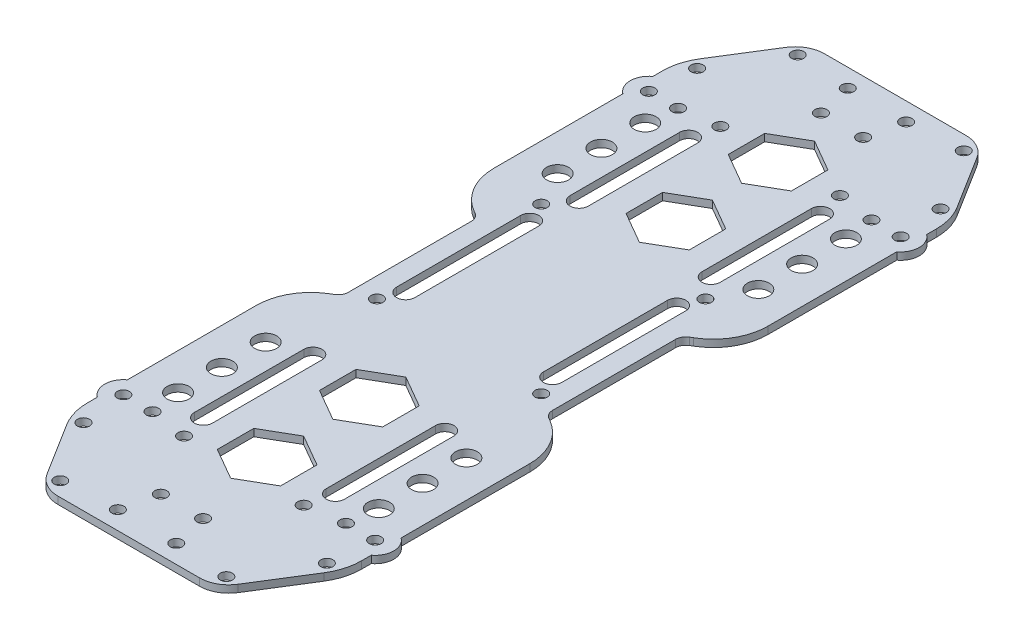
SolidWorks part; units mm, degrees
ref_plane "Front Plane" through (0, 0, 0) normal (0, 0, 1) x (1, 0, 0)
ref_plane "Top Plane" through (0, 0, 0) normal (0, 1, 0) x (1, 0, 0)
ref_plane "Right Plane" through (0, 0, 0) normal (1, 0, 0) x (0, 0, -1)
sketch "Sketch1" plane through (0, 0, 0) normal (0, 1, 0) x (1, 0, 0)
  line L0 (37.5251, 78.755) -> (37.5251, 32.6348)
  line L2 (-200, -200) -> (200, -200) construction
  line L7 (-200, -200) -> (-200, 200) construction
  line L11 (200, -200) -> (200, 200) construction
  line L14 (-200, -200) -> (200, 200) construction
  line L17 (0, 0) -> (60, 0) construction
  line L23 (0, 120) -> (0, -120) construction
  line L24 (0, 0) -> (-60, 0) construction
  line L69 (29.4047, 19.2862) -> (30.0251, 19.6444)
  line L70 (-30, -19.6299) -> (-29.4047, -19.2862)
  line L71 (-28, -16.8532) -> (-28, 16.8532)
  line L73 (37.5251, -32.6348) -> (37.5251, -78.755)
  line L74 (-29.4047, 19.2862) -> (-30, 19.6299)
  line L78 (28, -16.8532) -> (28, 16.8532)
  line L79 (30.0251, -19.6444) -> (29.4047, -19.2862)
  line L80 (-37.5, -32.6203) -> (-37.5, -78.7951)
  line L81 (-60, 36.9504) -> (-67.2154, 32.7846) [skipped]
  line L82 (-92, 0) -> (-92, -18.4752) [skipped]
  line L83 (-76, -27.7128) -> (-60, -36.9504) [skipped]
  line L84 (-200, 200) -> (200, -200) construction
  line L85 (-200, 200) -> (200, 200) construction
  line L86 (-22.7528, 101.0355) -> (-33.3512, 84.0745) construction
  line L87 (-28.052, 92.555) -> (-200, 200) construction
  line L88 (-33.3512, 84.0745) -> (-16.3903, 73.4761) construction
  line L89 (-16.3903, 73.4761) -> (-5.7919, 90.4371) construction
  line L90 (16.3903, 73.4761) -> (5.7919, 90.4371) construction
  line L91 (-19.3786, 105) -> (19.3786, 105)
  line L92 (-35.2207, 86.7439) -> (-26.163, 101.2394)
  line L93 (35.2458, 86.7038) -> (26.163, 101.2394)
  line L94 (-37.5, 78.7951) -> (-37.5, 32.6203)
  line L95 (35.2458, -86.7038) -> (26.163, -101.2394)
  line L96 (-19.3786, -105) -> (19.3786, -105)
  line L97 (-35.2207, -86.7439) -> (-26.163, -101.2394)
  line L98 (33.3512, 84.0745) -> (16.3903, 73.4761) construction
  line L99 (22.7528, 101.0355) -> (33.3512, 84.0745) construction
  line L100 (22.7528, -101.0355) -> (33.3512, -84.0745) construction
  line L101 (33.3512, -84.0745) -> (16.3903, -73.4761) construction
  line L102 (16.3903, -73.4761) -> (5.7919, -90.4371) construction
  line L103 (-16.3903, -73.4761) -> (-5.7919, -90.4371) construction
  line L104 (-33.3512, -84.0745) -> (-16.3903, -73.4761) construction
  line L105 (-22.7528, -101.0355) -> (-33.3512, -84.0745) construction
  circle A7 centre (200, 200) radius 177.8 construction
  circle A8 centre (-200, 200) radius 177.8 construction
  circle A9 centre (-200, -200) radius 177.8 construction
  circle A10 centre (200, -200) radius 177.8 construction
  circle A29 centre (-27.4977, 64) radius 3
  circle A30 centre (-27.4989, 52) radius 3
  circle A31 centre (-27.5, 40) radius 3
  circle A70 centre (27.5, 40) radius 3
  circle A71 centre (27.4989, 52) radius 3
  circle A72 centre (27.4977, 64) radius 3
  circle A73 centre (27.4977, -64) radius 3
  circle A74 centre (27.4989, -52) radius 3
  circle A75 centre (27.5, -40) radius 3
  circle A76 centre (-27.5, -40) radius 3
  circle A77 centre (-27.4989, -52) radius 3
  circle A78 centre (-27.4977, -64) radius 3
  circle A79 centre (-34.4977, 72) radius 1.65
  circle A80 centre (34.4977, 72) radius 1.65
  circle A82 centre (-34.4977, -72) radius 1.65
  circle A84 centre (-22.7528, 101.0355) radius 1.65
  circle A92 centre (22.7528, 101.0355) radius 3 construction
  circle A94 centre (5.7919, 90.4371) radius 3 construction
  circle A96 centre (16.3903, 73.4761) radius 3 construction
  circle A97 centre (33.3512, 84.0745) radius 3 construction
  circle A100 centre (33.3512, -84.0745) radius 3 construction
  circle A102 centre (16.3903, -73.4761) radius 3 construction
  circle A104 centre (22.7528, -101.0355) radius 3 construction
  circle A106 centre (5.7919, -90.4371) radius 3 construction
  circle A108 centre (-5.7919, -90.4371) radius 3 construction
  circle A110 centre (-16.3903, -73.4761) radius 3 construction
  circle A111 centre (-33.3512, -84.0745) radius 3 construction
  circle A114 centre (-22.7528, -101.0355) radius 3 construction
  arc A115 (26.163, 101.2394) -> (19.3786, 105) centre (19.3786, 97) ccw
  arc A116 (-19.3786, 105) -> (-26.163, 101.2394) centre (-19.3786, 97) ccw
  arc A117 (35.2458, 86.7038) -> (37.5251, 78.755) centre (22.5251, 78.755) cw
  arc A118 (-35.2207, 86.7439) -> (-37.5, 78.7951) centre (-22.5, 78.7951) ccw
  arc A119 (35.2458, -86.7038) -> (37.5251, -78.755) centre (22.5251, -78.755) ccw
  arc A120 (26.163, -101.2394) -> (19.3786, -105) centre (19.3786, -97) cw
  arc A121 (-19.3786, -105) -> (-26.163, -101.2394) centre (-19.3786, -97) cw
  arc A122 (-35.2207, -86.7439) -> (-37.5, -78.7951) centre (-22.5, -78.7951) cw
  arc A123 (-30, 19.6299) -> (-37.5, 32.6203) centre (-22.5, 32.6203) cw
  arc A124 (30.0251, 19.6444) -> (37.5251, 32.6348) centre (22.5251, 32.6348) ccw
  arc A125 (37.5251, -32.6348) -> (30.0251, -19.6444) centre (22.5251, -32.6348) ccw
  arc A126 (-30, -19.6299) -> (-37.5, -32.6203) centre (-22.5, -32.6203) ccw
  arc A127 (-28, 16.8532) -> (-29.4047, 19.2862) centre (-30.8094, 16.8532) ccw
  arc A128 (29.4047, 19.2862) -> (28, 16.8532) centre (30.8094, 16.8532) ccw
  arc A129 (28, -16.8532) -> (29.4047, -19.2862) centre (30.8094, -16.8532) ccw
  arc A130 (-29.4047, -19.2862) -> (-28, -16.8532) centre (-30.8094, -16.8532) ccw
  circle A131 centre (-33.3512, 84.0745) radius 1.65
  circle A132 centre (-5.7919, 90.4371) radius 1.65
  circle A133 centre (-16.3903, 73.4761) radius 1.65
  circle A134 centre (16.3903, 73.4761) radius 1.65
  circle A135 centre (5.7919, 90.4371) radius 1.65
  circle A136 centre (33.3512, 84.0745) radius 1.65
  circle A137 centre (22.7528, 101.0355) radius 1.65
  circle A138 centre (-16.3903, -73.4761) radius 1.65
  circle A139 centre (16.3903, -73.4761) radius 1.65
  circle A140 centre (33.3512, -84.0745) radius 3 construction
  circle A141 centre (5.7919, -90.4371) radius 3 construction
  circle A142 centre (22.7528, -101.0355) radius 3 construction
  circle A143 centre (22.7528, -101.0355) radius 1.65
  circle A144 centre (33.3512, -84.0745) radius 1.65
  circle A145 centre (5.7919, -90.4371) radius 1.65
  circle A146 centre (-5.7919, -90.4371) radius 1.65
  circle A147 centre (-33.3512, -84.0745) radius 1.65
  circle A148 centre (-22.7528, -101.0355) radius 1.65
  circle A149 centre (34.4977, -72) radius 1.65
  point P22 (0, 0)
  point P26 (-200, 200)
  point P54 (0, 0)
  point P151 (-28, 18.4752)
  point P154 (28, 18.4752)
  point P157 (28, -18.4752)
  point P160 (-28, -18.4752)
  dimension "D4" = 60
  dimension "D5" = 400
  dimension "D7" = 15
  dimension "D8" = 15
  dimension "D9" = 355.6
  dimension "D10" = 8
  dimension "D11" = 40
  dimension "D13" = 3.3
  dimension "D14" = 10
  dimension "D15" = 3.3
  dimension "D16" = 20
  dimension "D17" = 32
  dimension "D18" = 90
  dimension "D19" = 105
  dimension "D20" = 3.3
  dimension "D21" = 20
  dimension "D22" = 8
  dimension "D23" = 6
  dimension "D24" = 2.8094
  dimension "D25" = 90
  dimension "D26" = 90
  dimension "D27" = 12
  dimension "D28" = 12
  dimension "D29" = 20
  dimension "D6" = 60
  dimension "D12" = 7
  dimension "D3" = 400
extrude "Boss-Extrude1" add sketch "Sketch1" along normal blind 2
sketch "Sketch2" plane through (0, 2, 0) normal (0, 1, 0) x (1, 0, 0)
  line L33 (28, -16.8532) -> (28, 16.8532) construction
  line L36 (28, 0) -> (-28, 0) construction
  line L49 (-28, 16.8532) -> (-28, -16.8532) construction
  circle A11 centre (-34.4977, 72) radius 5.0909
  circle A12 centre (34.4977, 72) radius 5.0909
  circle A13 centre (34.4977, -72) radius 5.0909
  circle A14 centre (-34.4977, -72) radius 5.0909
  circle A15 centre (-34.4977, 72) radius 1.65
  circle A16 centre (34.4977, 72) radius 1.65
  circle A17 centre (34.4977, -72) radius 1.65
  circle A18 centre (-34.4977, -72) radius 1.65
extrude "Boss-Extrude2" add sketch "Sketch2" against normal up to surface (2 mm away)
sketch "Sketch3" plane through (0, 2, 0) normal (0, 1, 0) x (1, 0, 0)
  line L4 (-28, 0) -> (28, 0) construction
  line L5 (-28, 16.8532) -> (-28, -16.8532) construction
  line L6 (28, -16.8532) -> (28, 16.8532) construction
  line L31 (0, 82.9095) -> (-8.6603, 77.9095)
  line L38 (-8.6603, 77.9095) -> (-8.6603, 67.9095)
  line L39 (-8.6603, 67.9095) -> (0, 62.9095)
  line L40 (0, 62.9095) -> (8.6603, 67.9095)
  line L41 (8.6603, 67.9095) -> (8.6603, 77.9095)
  line L42 (8.6603, 77.9095) -> (0, 82.9095)
  line L43 (0, 54.9095) -> (-8.6603, 49.9095)
  line L44 (-8.6603, 49.9095) -> (-8.6603, 39.9095)
  line L45 (-8.6603, 39.9095) -> (0, 34.9095)
  line L46 (0, 34.9095) -> (8.6603, 39.9095)
  line L47 (8.6603, 39.9095) -> (8.6603, 49.9095)
  line L48 (8.6603, 49.9095) -> (0, 54.9095)
  line L49 (0, 26.9095) -> (-8.6603, 21.9095)
  line L50 (-8.6603, 21.9095) -> (-8.6603, 11.9095)
  line L51 (-8.6603, 11.9095) -> (0, 6.9095)
  line L52 (0, 6.9095) -> (8.6603, 11.9095)
  line L53 (8.6603, 11.9095) -> (8.6603, 21.9095)
  line L54 (8.6603, 21.9095) -> (0, 26.9095)
  line L55 (0, -1.0905) -> (-8.6603, -6.0905)
  line L56 (-8.6603, -6.0905) -> (-8.6603, -16.0905)
  line L57 (-8.6603, -16.0905) -> (0, -21.0905)
  line L58 (0, -21.0905) -> (8.6603, -16.0905)
  line L59 (8.6603, -16.0905) -> (8.6603, -6.0905)
  line L60 (8.6603, -6.0905) -> (0, -1.0905)
  line L61 (0, -29.0905) -> (-8.6603, -34.0905)
  line L62 (-8.6603, -34.0905) -> (-8.6603, -44.0905)
  line L63 (-8.6603, -44.0905) -> (0, -49.0905)
  line L64 (0, -49.0905) -> (8.6603, -44.0905)
  line L65 (8.6603, -44.0905) -> (8.6603, -34.0905)
  line L66 (8.6603, -34.0905) -> (0, -29.0905)
  line L67 (0, -57.0905) -> (-8.6603, -62.0905)
  line L68 (-8.6603, -62.0905) -> (-8.6603, -72.0905)
  line L69 (-8.6603, -72.0905) -> (0, -77.0905)
  line L70 (0, -77.0905) -> (8.6603, -72.0905)
  line L71 (8.6603, -72.0905) -> (8.6603, -62.0905)
  line L72 (8.6603, -62.0905) -> (0, -57.0905)
  circle A3 centre (-32.5, 28) radius 1.5
  circle A8 centre (32.5, 28) radius 1.5
  circle A12 centre (0, 72.9095) radius 8.6603 construction
  circle A13 centre (0, 44.9095) radius 8.6603 construction
  circle A24 centre (0, 16.9095) radius 8.6603 construction
  circle A25 centre (0, -11.0905) radius 8.6603 construction
  circle A26 centre (0, -39.0905) radius 8.6603 construction
  circle A27 centre (0, -67.0905) radius 8.6603 construction
  circle A39 centre (32.5, -28) radius 1.5
  circle A50 centre (-32.5, -28) radius 1.5
sketch "Sketch5" plane through (0, 2, 0) normal (0, 1, 0) x (1, 0, 0)
  line L0 (-19.3786, 105) -> (19.3786, 105) construction
  line L1 (0, 120) -> (0, -120) construction
  line L2 (0, 105) -> (0, -105) construction
  line L3 (-19.3786, -105) -> (19.3786, -105) construction
  line L4 (-18.0747, 66.4819) -> (-18.0747, 36.4819) construction
  line L5 (-60, 0) -> (60, 0) construction
  line L6 (-15.5747, 66.4819) -> (-15.5747, 36.4819)
  line L8 (-25.75, -34) -> (25.25, -34) construction
  line L9 (-25.75, -34) -> (-25.75, 34) construction
  line L10 (-25.75, 34) -> (25.25, 34) construction
  line L11 (25.25, -34) -> (25.25, 34) construction
  line L12 (-22.5, 30.5) -> (-22.5, -14.5) construction
  line L13 (-24.15, 30.5) -> (-25.75, 30.5) construction
  line L21 (-22.5, 30.5) -> (22.5, 30.5) construction
  line L22 (22.5, 30.5) -> (22.5, -14.5) construction
  line L23 (-20.5747, 66.4819) -> (-20.5747, 36.4819)
  line L24 (-20.1305, 25) -> (-20.1305, 8) construction
  line L25 (-20.1305, 8) -> (-20.1305, -9) construction
  line L26 (-20.1305, 25) -> (-20.1305, -9) construction
  line L27 (-17.6305, 25) -> (-17.6305, -9)
  line L28 (-22.6305, 25) -> (-22.6305, -9)
  line L29 (20.1305, 25) -> (20.1305, -9) construction
  line L30 (17.6305, 25) -> (17.6305, -9)
  line L31 (22.6305, 25) -> (22.6305, -9)
  line L32 (18.0747, 66.4819) -> (18.0747, 36.4819) construction
  line L33 (15.5747, 66.4819) -> (15.5747, 36.4819)
  line L34 (20.5747, 66.4819) -> (20.5747, 36.4819)
  line L35 (18.0747, -66.4819) -> (18.0747, -36.4819) construction
  line L36 (15.5747, -66.4819) -> (15.5747, -36.4819)
  line L37 (20.5747, -66.4819) -> (20.5747, -36.4819)
  line L38 (-18.0747, -66.4819) -> (-18.0747, -36.4819) construction
  line L39 (-15.5747, -66.4819) -> (-15.5747, -36.4819)
  line L40 (-20.5747, -66.4819) -> (-20.5747, -36.4819)
  line L42 (8.6603, 49.9095) -> (0, 54.9095)
  line L43 (0, 54.9095) -> (-8.6603, 49.9095)
  line L44 (-8.6603, 49.9095) -> (-8.6603, 39.9095)
  line L45 (-8.6603, 39.9095) -> (0, 34.9095)
  line L46 (0, 34.9095) -> (8.6603, 39.9095)
  line L47 (8.6603, 39.9095) -> (8.6603, 49.9095)
  line L48 (8.6603, -44.0905) -> (8.6603, -34.0905)
  line L49 (8.6603, -34.0905) -> (0, -29.0905)
  line L50 (0, -29.0905) -> (-8.6603, -34.0905)
  line L51 (-8.6603, -34.0905) -> (-8.6603, -44.0905)
  line L52 (-8.6603, -44.0905) -> (0, -49.0905)
  line L53 (0, -49.0905) -> (8.6603, -44.0905)
  line L54 (0, 62.9095) -> (8.6603, 67.9095)
  line L55 (8.6603, 67.9095) -> (8.6603, 77.9095)
  line L56 (8.6603, 77.9095) -> (0, 82.9095)
  line L57 (0, 82.9095) -> (-8.6603, 77.9095)
  line L58 (-8.6603, 77.9095) -> (-8.6603, 67.9095)
  line L59 (-8.6603, 67.9095) -> (0, 62.9095)
  line L60 (8.6603, -62.0905) -> (0, -57.0905)
  line L61 (0, -57.0905) -> (-8.6603, -62.0905)
  line L62 (-8.6603, -62.0905) -> (-8.6603, -72.0905)
  line L63 (-8.6603, -72.0905) -> (0, -77.0905)
  line L64 (0, -77.0905) -> (8.6603, -72.0905)
  line L65 (8.6603, -72.0905) -> (8.6603, -62.0905)
  circle A0 centre (-26.4977, 72) radius 1.65
  circle A1 centre (-34.4977, 72) radius 1.65 construction
  circle A2 centre (-34.4977, 72) radius 3.5 construction
  circle A3 centre (-8, 100) radius 1.65
  circle A5 centre (8, 100) radius 1.65
  circle A6 centre (26.4977, 72) radius 1.65
  circle A7 centre (26.4977, -72) radius 1.65
  circle A8 centre (8, -100) radius 1.65
  circle A9 centre (-8, -100) radius 1.65
  circle A10 centre (-26.4977, -72) radius 1.65
  circle A12 centre (-22.5, 30.5) radius 1.65
  circle A13 centre (22.5, 30.5) radius 1.65
  circle A14 centre (-22.5, -14.5) radius 1.65
  circle A15 centre (22.5, -14.5) radius 1.65
  arc A16 (-15.5747, 66.4819) -> (-20.5747, 66.4819) centre (-18.0747, 66.4819) ccw
  arc A17 (-20.5747, 36.4819) -> (-15.5747, 36.4819) centre (-18.0747, 36.4819) ccw
  arc A18 (-17.6305, 25) -> (-22.6305, 25) centre (-20.1305, 25) ccw
  arc A19 (-22.6305, -9) -> (-17.6305, -9) centre (-20.1305, -9) ccw
  arc A20 (17.6305, 25) -> (22.6305, 25) centre (20.1305, 25) cw
  arc A21 (22.6305, -9) -> (17.6305, -9) centre (20.1305, -9) cw
  arc A22 (15.5747, 66.4819) -> (20.5747, 66.4819) centre (18.0747, 66.4819) cw
  arc A23 (20.5747, 36.4819) -> (15.5747, 36.4819) centre (18.0747, 36.4819) cw
  arc A24 (15.5747, -66.4819) -> (20.5747, -66.4819) centre (18.0747, -66.4819) ccw
  arc A25 (20.5747, -36.4819) -> (15.5747, -36.4819) centre (18.0747, -36.4819) ccw
  arc A26 (-15.5747, -66.4819) -> (-20.5747, -66.4819) centre (-18.0747, -66.4819) cw
  arc A27 (-20.5747, -36.4819) -> (-15.5747, -36.4819) centre (-18.0747, -36.4819) cw
  circle A28 centre (0, 44.9095) radius 8.6603 construction
  circle A29 centre (0, -39.0905) radius 8.6603 construction
  circle A30 centre (0, 72.9095) radius 8.6603 construction
  circle A31 centre (0, -67.0905) radius 8.6603 construction
  point P38 (0, 0)
  point P52 (-18.0747, 51.4819)
  point P59 (-20.1305, 8)
  point P67 (20.1305, 8)
  point P74 (18.0747, 51.4819)
  point P81 (18.0747, -51.4819)
  point P88 (-18.0747, -51.4819)
  dimension "D2" = 3.3
  dimension "D3" = 8
  dimension "D4" = 5
  dimension "D5" = 3.3
  dimension "D6" = 8
  dimension "D9" = 6.5
  dimension "D10" = 3.3
  dimension "D12" = 22.5
  dimension "D13" = 45
  dimension "D15" = 17
  dimension "D1" = 8
  dimension "D7" = 68
  dimension "D8" = 51
  dimension "D11" = 45
  dimension "D14" = 45
  dimension "D16" = 17
extrude "Cut-Extrude1" cut sketch "Sketch5" against normal blind 2
